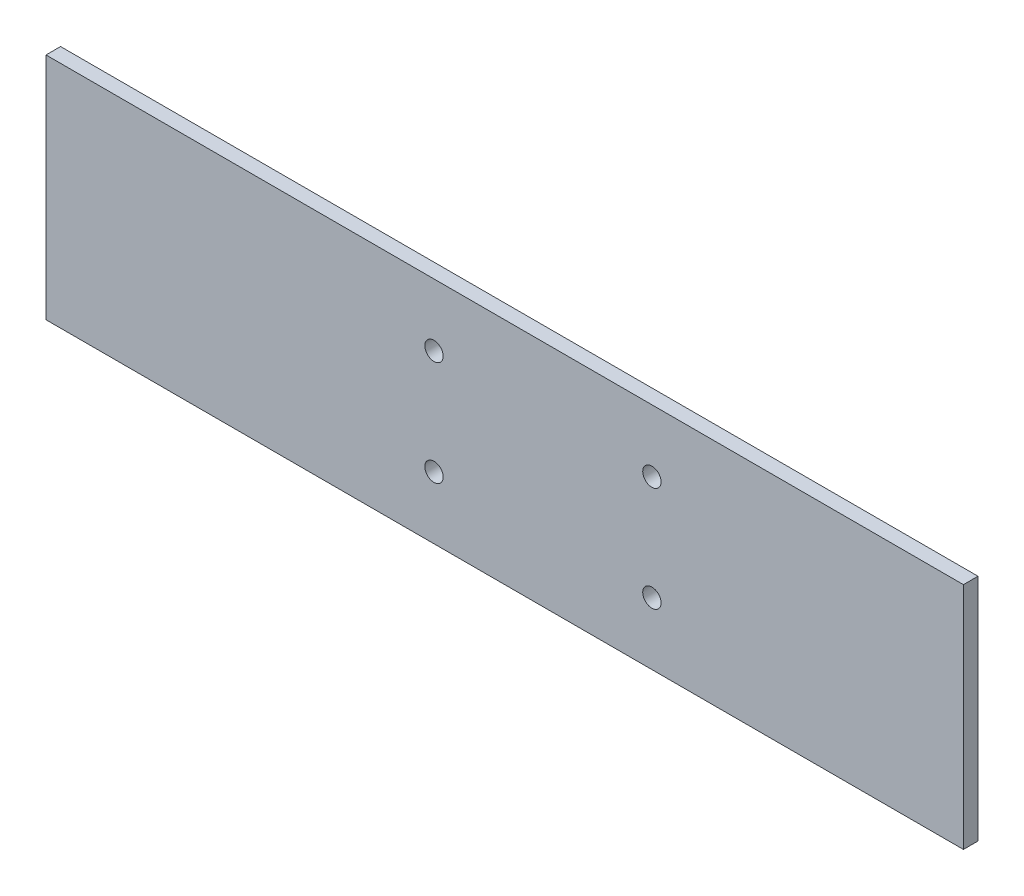
SolidWorks part; units mm, degrees
ref_plane "Front Plane" through (0, 0, 0) normal (0, 0, 1) x (1, 0, 0)
ref_plane "Top Plane" through (0, 0, 0) normal (0, 1, 0) x (1, 0, 0)
ref_plane "Right Plane" through (0, 0, 0) normal (1, 0, 0) x (0, 0, -1)
sketch "Sketch1" plane through (0, 0, 0) normal (0, 0, 1) x (1, 0, 0)
  line L1 (0, 0) -> (250, 0)
  line L2 (0, 0) -> (0, -150)
  line L3 (0, -150) -> (250, -150)
  line L4 (250, 0) -> (250, -150)
  circle A0 centre (53.75, -40.75) radius 6
  circle A1 centre (196.25, -40.75) radius 6
  circle A2 centre (196.25, -109.25) radius 6
  circle A3 centre (53.75, -109.25) radius 6
  dimension "D3" = 12
  dimension "D4" = 12
  dimension "D5" = 12
  dimension "D6" = 12
  dimension "D7" = 40.75
  dimension "D8" = 40.75
  dimension "D9" = 53.75
  dimension "D10" = 53.75
  dimension "D1" = 250
  dimension "D2" = 150
extrude "Boss-Extrude1" add sketch "Sketch1" along normal blind 9.525 contours L1 L4 L3 L2
sketch "Sketch2" plane through (0, 0, 0) normal (-1, 0, 0) x (0, 0, 1)
  line L1 (0, 0) -> (9.525, 0)
  line L2 (0, 0) -> (0, -150)
  line L3 (0, -150) -> (9.525, -150)
  line L4 (9.525, 0) -> (9.525, -150)
extrude "Boss-Extrude2" add sketch "Sketch2" along normal blind 200
sketch "Sketch3" plane through (250, 0, 0) normal (1, 0, 0) x (0, 0, -1)
  line L1 (-9.525, 0) -> (0, 0)
  line L2 (-9.525, 0) -> (-9.525, -150)
  line L3 (-9.525, -150) -> (0, -150)
  line L4 (0, 0) -> (0, -150)
extrude "Boss-Extrude3" add sketch "Sketch3" along normal blind 150
